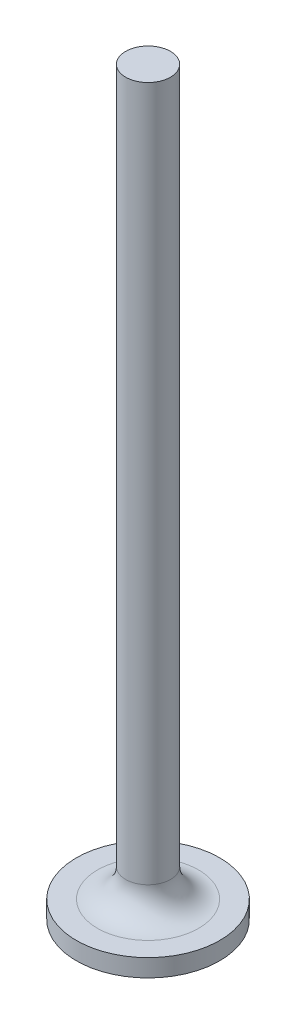
SolidWorks part; units mm, degrees
material "AISI 316 Annealed Stainless Steel Bar (SS)"
ref_plane "Front Plane" through (0, 0, 0) normal (0, 0, 1) x (1, 0, 0)
ref_plane "Top Plane" through (0, 0, 0) normal (0, 1, 0) x (1, 0, 0)
ref_plane "Right Plane" through (0, 0, 0) normal (1, 0, 0) x (0, 0, -1)
sketch "Sketch1" plane through (0, 0, 0) normal (0, 0, 1) x (1, 0, 0)
  line L0 (0, -31.8317) -> (0, 0) construction
  line L1 (0, 0) -> (10.16, 0)
  line L2 (10.16, 0) -> (10.16, 2.5)
  line L4 (3.175, 2.5) -> (3.175, 105)
  line L5 (3.175, 105) -> (0, 105)
  line L7 (0, 105) -> (0, 0)
  line L8 (10.16, 2.5) -> (3.175, 2.5)
  dimension "D1" = 10.16
  dimension "D2" = 3.175
  dimension "D3" = 2.5
  dimension "D4" = 105
revolve "Revolve1" add sketch "Sketch1" angle 360 about L0
cosmetic thread "Cosmetic Thread1" parameters "D1"=12, "D2"=5.268
sketch "Sketch2" [suppressed] plane through (0, 2.5, 0) normal (0, 1, 0) x (1, 0, 0)
  line L0 (-0.75, 10.1323) -> (-0.75, 0)
  line L1 (-0.75, 0) -> (0.75, 0)
  line L2 (0.75, 0) -> (0.75, 10.1323)
  circle A0 centre (0, 0) radius 10.16 construction
  arc A1 (0.75, 10.1323) -> (-0.75, 10.1323) centre (0, 0) ccw
  point P7 (0, 0)
  dimension "D1" = 1.5
extrude "Boss-Extrude1" [suppressed] add sketch "Sketch2" along normal blind 12
pattern_circular "CirPattern1" [suppressed] count 3 over 360
sketch "Sketch3" [suppressed] plane through (0, 14.5, 0) normal (0, 1, 0) x (1, 0, 0)
  circle A0 centre (0, 0) radius 7.475
  dimension "D1" = 14.95
extrude "Cut-Extrude2" [suppressed] cut sketch "Sketch3" against normal up to surface (12 mm away) flip side to cut
fillet "Fillet1" radius 4 1 edges at (0, 2.5, -3.175)
